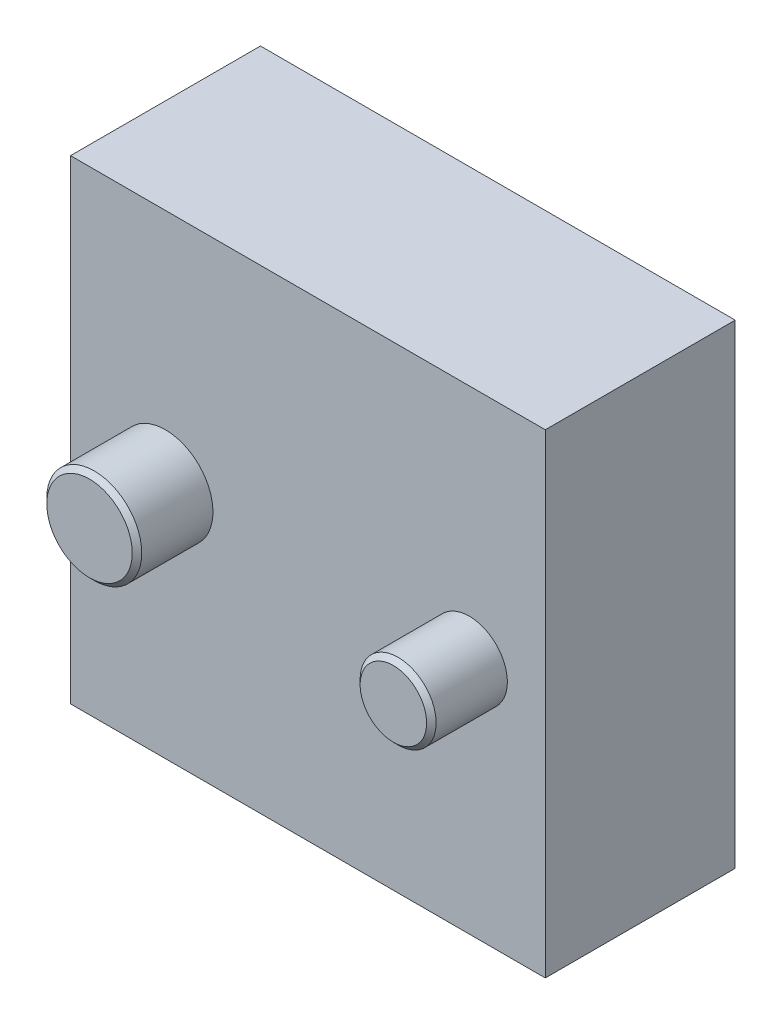
SolidWorks part; units mm, degrees
ref_plane "前视基准面" through (0, 0, 0) normal (0, 0, 1) x (1, 0, 0)
ref_plane "上视基准面" through (0, 0, 0) normal (0, 1, 0) x (1, 0, 0)
ref_plane "右视基准面" through (0, 0, 0) normal (1, 0, 0) x (0, 0, -1)
sketch "草图3" plane through (0, 0, 0) normal (0, 0, 1) x (1, 0, 0)
  line L1 (-25, -25) -> (25, -25)
  line L2 (-25, -25) -> (-25, 25)
  line L3 (-25, 25) -> (25, 25)
  line L4 (25, -25) -> (25, 25)
  line L5 (0, 25) -> (0, -25) construction
  line L6 (-25, 0) -> (25, 0) construction
  point P0 (0, 0)
  dimension "D1" = 50
  dimension "D2" = 50
extrude "凸台-拉伸3" add sketch "草图3" along normal blind 20
sketch "草图4" plane through (0, 0, 20) normal (0, 0, 1) x (1, 0, 0)
  circle A0 centre (-15, 0) radius 5
  circle A1 centre (17, 0) radius 4
extrude "凸台-拉伸4" add sketch "草图4" along normal blind 8
chamfer "倒角2" distance 0.5 angle 45 1 edges at (-10, 0, 28)
chamfer "倒角3" distance 0.5 angle 45 1 edges at (21, 0, 28)
